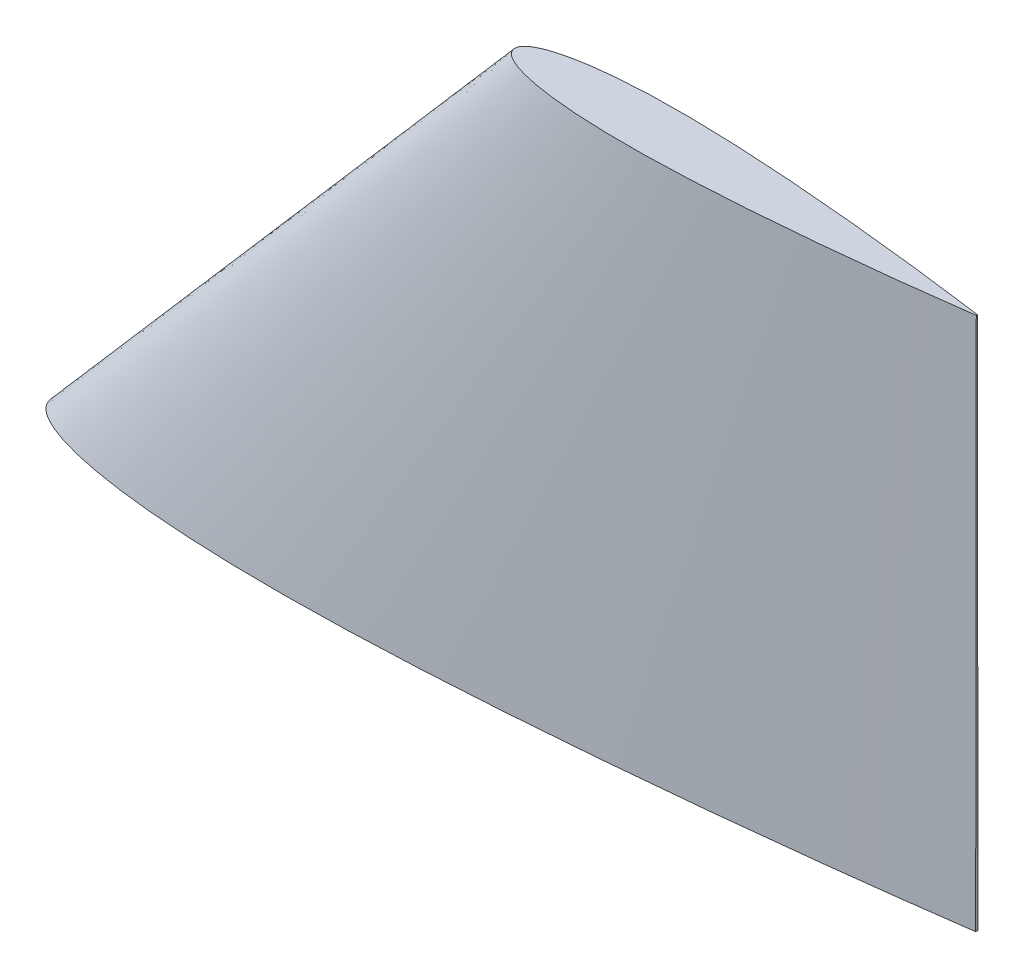
SolidWorks part; units mm, degrees
ref_plane "Front Plane" through (0, 0, 0) normal (0, 0, 1) x (1, 0, 0)
ref_plane "Top Plane" through (0, 0, 0) normal (0, 1, 0) x (1, 0, 0)
ref_plane "Right Plane" through (0, 0, 0) normal (1, 0, 0) x (0, 0, -1)
curve "Curve3"
  spline degree 3 poles (25.4, 0, 0.032) (25.3951, 0, 0.0327) (25.3753, 0, 0.0355) (25.3309, 0, 0.0417) (25.257, 0, 0.052) (25.1537, 0, 0.0664) (25.0214, 0, 0.0846) (24.8603, 0, 0.1068) (24.6708, 0, 0.1326) (24.4533, 0, 0.1619) (24.2084, 0, 0.1946) (23.9366, 0, 0.2304) (23.6385, 0, 0.2691) (23.3149, 0, 0.3106) (22.9666, 0, 0.3545) (22.5942, 0, 0.4008) (22.1987, 0, 0.449) (21.7811, 0, 0.499) (21.3422, 0, 0.5505) (20.8832, 0, 0.6032) (20.405, 0, 0.6571) (19.9089, 0, 0.7116) (19.3959, 0, 0.7667) (18.8673, 0, 0.8219) (18.3242, 0, 0.8772) (17.7681, 0, 0.9321) (17.2001, 0, 0.9864) (16.6216, 0, 1.0399) (16.0339, 0, 1.0922) (15.4384, 0, 1.143) (14.8366, 0, 1.1921) (14.2297, 0, 1.2391) (13.6193, 0, 1.2836) (13.0067, 0, 1.3254) (12.3935, 0, 1.3642) (11.7809, 0, 1.3995) (11.1705, 0, 1.4311) (10.5636, 0, 1.4587) (9.9618, 0, 1.4818) (9.3663, 0, 1.5004) (8.7786, 0, 1.514) (8.2001, 0, 1.5224) (7.632, 0, 1.5254) (7.0758, 0, 1.5227) (6.5327, 0, 1.5144) (6.0041, 0, 1.5) (5.491, 0, 1.4798) (4.9948, 0, 1.4535) (4.5166, 0, 1.4212) (4.0575, 0, 1.3829) (3.6185, 0, 1.3388) (3.2008, 0, 1.2888) (2.8052, 0, 1.2334) (2.4327, 0, 1.1725) (2.0841, 0, 1.1064) (1.7603, 0, 1.0355) (1.462, 0, 0.96) (1.1898, 0, 0.8801) (0.9445, 0, 0.7962) (0.7264, 0, 0.7086) (0.536, 0, 0.6175) (0.3737, 0, 0.523) (0.2396, 0, 0.4254) (0.1341, 0, 0.3245) (0.0574, 0, 0.22) (0.0105, 0, 0.1114) (-0.0051, 0, 0) (0.0105, 0, -0.1114) (0.0574, 0, -0.22) (0.1341, 0, -0.3245) (0.2396, 0, -0.4254) (0.3737, 0, -0.523) (0.536, 0, -0.6175) (0.7264, 0, -0.7086) (0.9445, 0, -0.7962) (1.1898, 0, -0.8801) (1.462, 0, -0.96) (1.7603, 0, -1.0355) (2.0841, 0, -1.1064) (2.4327, 0, -1.1725) (2.8052, 0, -1.2334) (3.2008, 0, -1.2888) (3.6185, 0, -1.3388) (4.0575, 0, -1.3829) (4.5166, 0, -1.4212) (4.9948, 0, -1.4535) (5.491, 0, -1.4798) (6.0041, 0, -1.5) (6.5327, 0, -1.5144) (7.0758, 0, -1.5227) (7.632, 0, -1.5254) (8.2001, 0, -1.5224) (8.7786, 0, -1.514) (9.3663, 0, -1.5004) (9.9618, 0, -1.4818) (10.5636, 0, -1.4587) (11.1705, 0, -1.4311) (11.7809, 0, -1.3995) (12.3935, 0, -1.3642) (13.0067, 0, -1.3254) (13.6193, 0, -1.2836) (14.2297, 0, -1.2391) (14.8366, 0, -1.1921) (15.4384, 0, -1.143) (16.0339, 0, -1.0922) (16.6216, 0, -1.0399) (17.2001, 0, -0.9864) (17.7681, 0, -0.9321) (18.3242, 0, -0.8772) (18.8673, 0, -0.8219) (19.3959, 0, -0.7667) (19.9089, 0, -0.7116) (20.405, 0, -0.6571) (20.8832, 0, -0.6032) (21.3422, 0, -0.5505) (21.7811, 0, -0.499) (22.1987, 0, -0.449) (22.5942, 0, -0.4008) (22.9666, 0, -0.3545) (23.3149, 0, -0.3106) (23.6385, 0, -0.2691) (23.9366, 0, -0.2304) (24.2084, 0, -0.1946) (24.4533, 0, -0.1619) (24.6708, 0, -0.1326) (24.8603, 0, -0.1068) (25.0214, 0, -0.0846) (25.1537, 0, -0.0664) (25.257, 0, -0.052) (25.3309, 0, -0.0417) (25.3753, 0, -0.0355) (25.3951, 0, -0.0327) (25.4, 0, -0.032) knots 0 0 0 0 0.000289 0.001156 0.002598 0.004612 0.007194 0.010336 0.014031 0.018272 0.023046 0.028343 0.03415 0.040454 0.047238 0.054489 0.062187 0.070314 0.078852 0.08778 0.097078 0.106722 0.116691 0.126961 0.137507 0.148306 0.159331 0.170556 0.181957 0.193504 0.205171 0.216932 0.228758 0.240621 0.252495 0.26435 0.276161 0.287898 0.299536 0.311047 0.322405 0.333584 0.344559 0.355306 0.3658 0.376018 0.385937 0.395538 0.404798 0.413699 0.422221 0.430349 0.438066 0.445357 0.452209 0.458612 0.464554 0.47003 0.475035 0.479569 0.483637 0.48725 0.490431 0.493219 0.495674 0.497891 0.5 0.502109 0.504326 0.506781 0.509569 0.51275 0.516363 0.520431 0.524965 0.52997 0.535446 0.541388 0.547791 0.554643 0.561934 0.569651 0.577779 0.586301 0.595202 0.604462 0.614063 0.623982 0.6342 0.644694 0.655441 0.666416 0.677595 0.688953 0.700464 0.712102 0.723839 0.73565 0.747505 0.759379 0.771242 0.783068 0.794829 0.806496 0.818043 0.829444 0.840669 0.851694 0.862493 0.873039 0.883309 0.893278 0.902922 0.91222 0.921148 0.929686 0.937813 0.945511 0.952762 0.959546 0.96585 0.971657 0.976954 0.981728 0.985969 0.989664 0.992806 0.995388 0.997402 0.998844 0.999711 1 1 1 1
sketch "Sketch3" plane through (0, 0, 0) normal (0, 1, 0) x (1, 0, 0)
  line L1 (76.2, 0) -> (0, 0) construction
  line L2 (76.2, 0.096) -> (76.2, -0.096)
  spline S1 degree 3 poles (76.2, -0.096) (76.1852, -0.0981) (76.1259, -0.1064) (75.8893, -0.1395) (75.5351, -0.189) (75.0641, -0.2539) (74.5808, -0.3204) (74.0123, -0.3978) (73.3598, -0.4857) (72.6251, -0.5837) (71.8097, -0.6911) (70.9156, -0.8074) (69.9448, -0.9317) (68.5041, -1.1135) (66.9691, -1.3023) (65.3433, -1.4969) (64.0267, -1.6515) (62.6495, -1.8097) (61.2151, -1.9712) (59.7266, -2.1348) (58.1877, -2.3) (56.6018, -2.4657) (54.9727, -2.6315) (53.3042, -2.7962) (51.6002, -2.9593) (49.8647, -3.1196) (48.1017, -3.2767) (46.3153, -3.4291) (44.5097, -3.5763) (42.6892, -3.7173) (40.8579, -3.8509) (39.0202, -3.9763) (37.1804, -4.0926) (34.7358, -4.2335) (32.3021, -4.3524) (29.2974, -4.4681) (26.9319, -4.5333) (24.6002, -4.5672) (22.8961, -4.5761) (21.2275, -4.5682) (19.5982, -4.5431) (18.0122, -4.5001) (16.4731, -4.4394) (14.9845, -4.3605) (13.5498, -4.2636) (12.1724, -4.1488) (10.8556, -4.0163) (9.6023, -3.8665) (8.4156, -3.7001) (7.2981, -3.5174) (6.2524, -3.3193) (5.2809, -3.1066) (4.386, -2.88) (3.5695, -2.6404) (2.8334, -2.3887) (2.1791, -2.1258) (1.6079, -1.8524) (1.121, -1.569) (0.7189, -1.2762) (0.4023, -0.9735) (0.1722, -0.6601) (0.0314, -0.3343) (-0.0153, 0) (0.0314, 0.3343) (0.1722, 0.6601) (0.4023, 0.9735) (0.7189, 1.2762) (1.121, 1.569) (1.6079, 1.8524) (2.1791, 2.1258) (2.8334, 2.3887) (3.5695, 2.6404) (4.386, 2.88) (5.2809, 3.1066) (6.2524, 3.3193) (7.2981, 3.5174) (8.4156, 3.7001) (9.6023, 3.8665) (10.8556, 4.0163) (12.1724, 4.1488) (13.5498, 4.2636) (14.9845, 4.3605) (16.4731, 4.4394) (18.0122, 4.5001) (19.5982, 4.5431) (21.2275, 4.5682) (22.8961, 4.5761) (24.6002, 4.5672) (26.9319, 4.5333) (29.9052, 4.4514) (32.9095, 4.3245) (35.3427, 4.1985) (37.1804, 4.0926) (39.0202, 3.9763) (40.8579, 3.8509) (42.6892, 3.7173) (44.5097, 3.5763) (46.3153, 3.4291) (48.1017, 3.2767) (49.8647, 3.1196) (51.6002, 2.9593) (53.3042, 2.7962) (54.9727, 2.6315) (56.6018, 2.4657) (58.1877, 2.3) (59.7266, 2.1348) (61.2151, 1.9712) (62.6495, 1.8097) (64.0267, 1.6515) (65.3433, 1.4969) (66.9691, 1.3023) (68.5041, 1.1135) (69.9448, 0.9317) (70.9156, 0.8074) (71.8097, 0.6911) (72.6251, 0.5837) (73.3598, 0.4857) (74.0123, 0.3978) (74.5808, 0.3204) (75.0641, 0.2539) (75.5351, 0.189) (75.8893, 0.1395) (76.1259, 0.1064) (76.1852, 0.0981) (76.2, 0.096) knots 0 0 0 0 0.000289 0.001156 0.004612 0.007194 0.010336 0.014031 0.018272 0.023046 0.028343 0.03415 0.040454 0.047238 0.062187 0.070314 0.078852 0.08778 0.097078 0.106722 0.116691 0.126961 0.137507 0.148306 0.159331 0.170556 0.181957 0.193504 0.205171 0.216932 0.228758 0.240621 0.252495 0.26435 0.287898 0.299536 0.322405 0.333584 0.344559 0.355306 0.3658 0.376018 0.385937 0.395538 0.404798 0.413699 0.422221 0.430349 0.438066 0.445357 0.452209 0.458612 0.464554 0.47003 0.475035 0.479569 0.483637 0.48725 0.490431 0.493219 0.495674 0.497891 0.5 0.502109 0.504326 0.506781 0.509569 0.51275 0.516363 0.520431 0.524965 0.52997 0.535446 0.541388 0.547791 0.554643 0.561934 0.569651 0.577779 0.586301 0.595202 0.604462 0.614063 0.623982 0.6342 0.644694 0.655441 0.666416 0.677595 0.700464 0.723839 0.73565 0.747505 0.759379 0.771242 0.783068 0.794829 0.806496 0.818043 0.829444 0.840669 0.851694 0.862493 0.873039 0.883309 0.893278 0.902922 0.91222 0.921148 0.929686 0.937813 0.952762 0.959546 0.96585 0.971657 0.976954 0.981728 0.985969 0.989664 0.992806 0.995388 0.998844 0.999711 1 1 1 1
  dimension "D1" = 76.2
sketch "Sketch4" plane through (0, 0, 0) normal (0, 0, 1) x (1, 0, 0)
  line L0 (76.2, 0) -> (76.2, 43.9941)
  line L1 (76.2, 0) -> (0, 0) construction
  line L2 (76.2, 43.9941) -> (38.1, 43.9941) construction
  line L3 (0, 0) -> (38.1, 43.9941)
  line L4 (0, 0) -> (76.2, 0) construction
  dimension "D1" = 43.9941
  dimension "D2" = 38.1
ref_plane "Plane1" through (0, 43.9941, 0) normal (0, 1, 0) x (1, 0, 0)
curve "Curve4"
  spline degree 3 poles (25.4, 0, 0.032) (25.3951, 0, 0.0327) (25.3753, 0, 0.0355) (25.3309, 0, 0.0417) (25.257, 0, 0.052) (25.1537, 0, 0.0664) (25.0214, 0, 0.0846) (24.8603, 0, 0.1068) (24.6708, 0, 0.1326) (24.4533, 0, 0.1619) (24.2084, 0, 0.1946) (23.9366, 0, 0.2304) (23.6385, 0, 0.2691) (23.3149, 0, 0.3106) (22.9666, 0, 0.3545) (22.5942, 0, 0.4008) (22.1987, 0, 0.449) (21.7811, 0, 0.499) (21.3422, 0, 0.5505) (20.8832, 0, 0.6032) (20.405, 0, 0.6571) (19.9089, 0, 0.7116) (19.3959, 0, 0.7667) (18.8673, 0, 0.8219) (18.3242, 0, 0.8772) (17.7681, 0, 0.9321) (17.2001, 0, 0.9864) (16.6216, 0, 1.0399) (16.0339, 0, 1.0922) (15.4384, 0, 1.143) (14.8366, 0, 1.1921) (14.2297, 0, 1.2391) (13.6193, 0, 1.2836) (13.0067, 0, 1.3254) (12.3935, 0, 1.3642) (11.7809, 0, 1.3995) (11.1705, 0, 1.4311) (10.5636, 0, 1.4587) (9.9618, 0, 1.4818) (9.3663, 0, 1.5004) (8.7786, 0, 1.514) (8.2001, 0, 1.5224) (7.632, 0, 1.5254) (7.0758, 0, 1.5227) (6.5327, 0, 1.5144) (6.0041, 0, 1.5) (5.491, 0, 1.4798) (4.9948, 0, 1.4535) (4.5166, 0, 1.4212) (4.0575, 0, 1.3829) (3.6185, 0, 1.3388) (3.2008, 0, 1.2888) (2.8052, 0, 1.2334) (2.4327, 0, 1.1725) (2.0841, 0, 1.1064) (1.7603, 0, 1.0355) (1.462, 0, 0.96) (1.1898, 0, 0.8801) (0.9445, 0, 0.7962) (0.7264, 0, 0.7086) (0.536, 0, 0.6175) (0.3737, 0, 0.523) (0.2396, 0, 0.4254) (0.1341, 0, 0.3245) (0.0574, 0, 0.22) (0.0105, 0, 0.1114) (-0.0051, 0, 0) (0.0105, 0, -0.1114) (0.0574, 0, -0.22) (0.1341, 0, -0.3245) (0.2396, 0, -0.4254) (0.3737, 0, -0.523) (0.536, 0, -0.6175) (0.7264, 0, -0.7086) (0.9445, 0, -0.7962) (1.1898, 0, -0.8801) (1.462, 0, -0.96) (1.7603, 0, -1.0355) (2.0841, 0, -1.1064) (2.4327, 0, -1.1725) (2.8052, 0, -1.2334) (3.2008, 0, -1.2888) (3.6185, 0, -1.3388) (4.0575, 0, -1.3829) (4.5166, 0, -1.4212) (4.9948, 0, -1.4535) (5.491, 0, -1.4798) (6.0041, 0, -1.5) (6.5327, 0, -1.5144) (7.0758, 0, -1.5227) (7.632, 0, -1.5254) (8.2001, 0, -1.5224) (8.7786, 0, -1.514) (9.3663, 0, -1.5004) (9.9618, 0, -1.4818) (10.5636, 0, -1.4587) (11.1705, 0, -1.4311) (11.7809, 0, -1.3995) (12.3935, 0, -1.3642) (13.0067, 0, -1.3254) (13.6193, 0, -1.2836) (14.2297, 0, -1.2391) (14.8366, 0, -1.1921) (15.4384, 0, -1.143) (16.0339, 0, -1.0922) (16.6216, 0, -1.0399) (17.2001, 0, -0.9864) (17.7681, 0, -0.9321) (18.3242, 0, -0.8772) (18.8673, 0, -0.8219) (19.3959, 0, -0.7667) (19.9089, 0, -0.7116) (20.405, 0, -0.6571) (20.8832, 0, -0.6032) (21.3422, 0, -0.5505) (21.7811, 0, -0.499) (22.1987, 0, -0.449) (22.5942, 0, -0.4008) (22.9666, 0, -0.3545) (23.3149, 0, -0.3106) (23.6385, 0, -0.2691) (23.9366, 0, -0.2304) (24.2084, 0, -0.1946) (24.4533, 0, -0.1619) (24.6708, 0, -0.1326) (24.8603, 0, -0.1068) (25.0214, 0, -0.0846) (25.1537, 0, -0.0664) (25.257, 0, -0.052) (25.3309, 0, -0.0417) (25.3753, 0, -0.0355) (25.3951, 0, -0.0327) (25.4, 0, -0.032) knots 0 0 0 0 0.000289 0.001156 0.002598 0.004612 0.007194 0.010336 0.014031 0.018272 0.023046 0.028343 0.03415 0.040454 0.047238 0.054489 0.062187 0.070314 0.078852 0.08778 0.097078 0.106722 0.116691 0.126961 0.137507 0.148306 0.159331 0.170556 0.181957 0.193504 0.205171 0.216932 0.228758 0.240621 0.252495 0.26435 0.276161 0.287898 0.299536 0.311047 0.322405 0.333584 0.344559 0.355306 0.3658 0.376018 0.385937 0.395538 0.404798 0.413699 0.422221 0.430349 0.438066 0.445357 0.452209 0.458612 0.464554 0.47003 0.475035 0.479569 0.483637 0.48725 0.490431 0.493219 0.495674 0.497891 0.5 0.502109 0.504326 0.506781 0.509569 0.51275 0.516363 0.520431 0.524965 0.52997 0.535446 0.541388 0.547791 0.554643 0.561934 0.569651 0.577779 0.586301 0.595202 0.604462 0.614063 0.623982 0.6342 0.644694 0.655441 0.666416 0.677595 0.688953 0.700464 0.712102 0.723839 0.73565 0.747505 0.759379 0.771242 0.783068 0.794829 0.806496 0.818043 0.829444 0.840669 0.851694 0.862493 0.873039 0.883309 0.893278 0.902922 0.91222 0.921148 0.929686 0.937813 0.945511 0.952762 0.959546 0.96585 0.971657 0.976954 0.981728 0.985969 0.989664 0.992806 0.995388 0.997402 0.998844 0.999711 1 1 1 1
sketch "Sketch5" plane through (0, 43.9941, 0) normal (0, 1, 0) x (1, 0, 0)
  line L1 (76.2, 0) -> (38.1, 0) construction
  line L2 (76.2, 0) -> (0, 0) construction
  line L3 (76.2, 0.048) -> (76.2, -0.048)
  spline S1 degree 3 poles (76.2, -0.048) (76.1926, -0.049) (76.1629, -0.0532) (76.0446, -0.0698) (75.8676, -0.0945) (75.6321, -0.127) (75.3904, -0.1602) (75.1061, -0.1989) (74.7799, -0.2429) (74.4125, -0.2919) (74.0049, -0.3456) (73.5578, -0.4037) (73.0724, -0.4659) (72.3521, -0.5568) (71.5845, -0.6511) (70.7716, -0.7484) (70.1134, -0.8257) (69.4248, -0.9049) (68.7075, -0.9856) (67.9633, -1.0674) (67.1938, -1.15) (66.4009, -1.2328) (65.5864, -1.3157) (64.7521, -1.3981) (63.9001, -1.4797) (63.0323, -1.5598) (62.1508, -1.6383) (61.2576, -1.7146) (60.3549, -1.7882) (59.4446, -1.8586) (58.529, -1.9254) (57.6101, -1.9882) (56.6902, -2.0463) (55.4679, -2.1168) (54.2511, -2.1762) (52.7487, -2.2341) (51.566, -2.2666) (50.4001, -2.2836) (49.548, -2.288) (48.7137, -2.2841) (47.8991, -2.2716) (47.1061, -2.2501) (46.3366, -2.2197) (45.5922, -2.1802) (44.8749, -2.1318) (44.1862, -2.0744) (43.5278, -2.0081) (42.9012, -1.9332) (42.3078, -1.8501) (41.749, -1.7587) (41.2262, -1.6597) (40.7405, -1.5533) (40.293, -1.44) (39.8848, -1.3202) (39.5167, -1.1944) (39.1895, -1.0629) (38.904, -0.9262) (38.6605, -0.7845) (38.4594, -0.6381) (38.3012, -0.4868) (38.1861, -0.33) (38.1157, -0.1671) (38.0923, 0) (38.1157, 0.1671) (38.1861, 0.33) (38.3012, 0.4868) (38.4594, 0.6381) (38.6605, 0.7845) (38.904, 0.9262) (39.1895, 1.0629) (39.5167, 1.1944) (39.8848, 1.3202) (40.293, 1.44) (40.7405, 1.5533) (41.2262, 1.6597) (41.749, 1.7587) (42.3078, 1.8501) (42.9012, 1.9332) (43.5278, 2.0081) (44.1862, 2.0744) (44.8749, 2.1318) (45.5922, 2.1802) (46.3366, 2.2197) (47.1061, 2.2501) (47.8991, 2.2716) (48.7137, 2.2841) (49.548, 2.288) (50.4001, 2.2836) (51.566, 2.2666) (53.0526, 2.2257) (54.5547, 2.1623) (55.7713, 2.0993) (56.6902, 2.0463) (57.6101, 1.9882) (58.529, 1.9254) (59.4446, 1.8586) (60.3549, 1.7882) (61.2576, 1.7146) (62.1508, 1.6383) (63.0323, 1.5598) (63.9001, 1.4797) (64.7521, 1.3981) (65.5864, 1.3157) (66.4009, 1.2328) (67.1938, 1.15) (67.9633, 1.0674) (68.7075, 0.9856) (69.4248, 0.9049) (70.1134, 0.8257) (70.7716, 0.7484) (71.5845, 0.6511) (72.3521, 0.5568) (73.0724, 0.4659) (73.5578, 0.4037) (74.0049, 0.3456) (74.4125, 0.2919) (74.7799, 0.2429) (75.1061, 0.1989) (75.3904, 0.1602) (75.6321, 0.127) (75.8676, 0.0945) (76.0446, 0.0698) (76.1629, 0.0532) (76.1926, 0.049) (76.2, 0.048) knots 0 0 0 0 0.000289 0.001156 0.004612 0.007194 0.010336 0.014031 0.018272 0.023046 0.028343 0.03415 0.040454 0.047238 0.062187 0.070314 0.078852 0.08778 0.097078 0.106722 0.116691 0.126961 0.137507 0.148306 0.159331 0.170556 0.181957 0.193504 0.205171 0.216932 0.228758 0.240621 0.252495 0.26435 0.287898 0.299536 0.322405 0.333584 0.344559 0.355306 0.3658 0.376018 0.385937 0.395538 0.404798 0.413699 0.422221 0.430349 0.438066 0.445357 0.452209 0.458612 0.464554 0.47003 0.475035 0.479569 0.483637 0.48725 0.490431 0.493219 0.495674 0.497891 0.5 0.502109 0.504326 0.506781 0.509569 0.51275 0.516363 0.520431 0.524965 0.52997 0.535446 0.541388 0.547791 0.554643 0.561934 0.569651 0.577779 0.586301 0.595202 0.604462 0.614063 0.623982 0.6342 0.644694 0.655441 0.666416 0.677595 0.700464 0.723839 0.73565 0.747505 0.759379 0.771242 0.783068 0.794829 0.806496 0.818043 0.829444 0.840669 0.851694 0.862493 0.873039 0.883309 0.893278 0.902922 0.91222 0.921148 0.929686 0.937813 0.952762 0.959546 0.96585 0.971657 0.976954 0.981728 0.985969 0.989664 0.992806 0.995388 0.998844 0.999711 1 1 1 1
  dimension "D1" = 38.1
loft "Loft11" add profiles "Sketch5", "Sketch3"
sketch "Sketch8" plane through (0, 0, 0) normal (0, 0, 1) x (1, 0, 0)
  line L0 (20.955, 0) -> (20.955, 12.7)
  line L1 (0, 0) -> (76.2, 0) construction
  line L5 (19.05, 15.9996) -> (20.955, 12.7)
  line L6 (19.05, 15.9996) -> (19.05, 0)
  line L7 (19.05, 0) -> (20.955, 0)
  dimension "D1" = 30
  dimension "D2" = 12.7
  dimension "D3" = 1.905
  dimension "D4" = 19.05
revolve "Cut-Revolve1" cut sketch "Sketch8" angle 360 about L6
sketch "Sketch9" plane through (0, 0, 0) normal (0, 0, 1) x (1, 0, 0)
  line L5 (22.225, 0) -> (22.225, 12.9087) construction
  line L6 (0, 0) -> (76.2, 0) construction
  dimension "D1" = 3.175
ref_plane "Plane2" through (22.225, 0, 0) normal (1, 0, 0) x (0, 0, -1)
mirror "Mirror1" about plane through (22.225, 0, 0) normal (1, 0, 0) of "Cut-Revolve1"
ref_plane "Plane3" through (28.575, 0, 0) normal (1, 0, 0) x (0, 0, -1)
mirror "Mirror2" about plane through (28.575, 0, 0) normal (1, 0, 0) of "Cut-Revolve1", "Mirror1"
